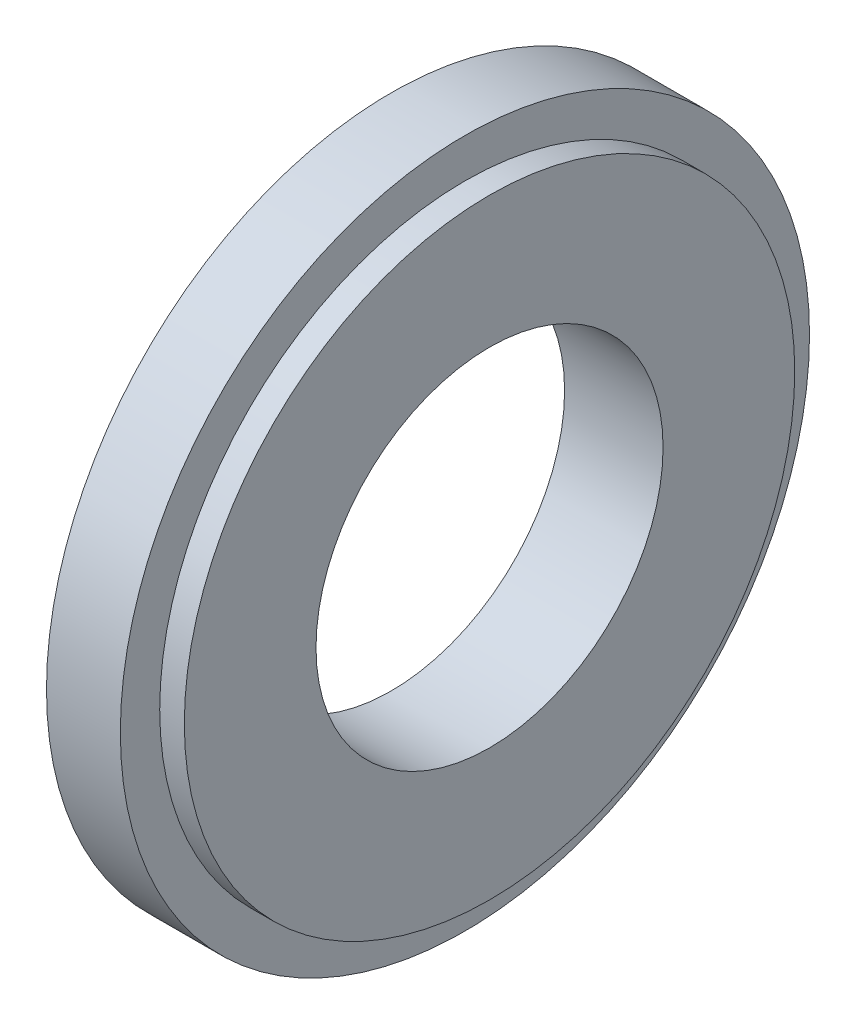
SolidWorks part; units mm, degrees
material "PEI"
ref_plane "Płaszczyzna przednia" through (0, 0, 0) normal (0, 0, 1) x (1, 0, 0)
ref_plane "Płaszczyzna górna" through (0, 0, 0) normal (0, 1, 0) x (1, 0, 0)
ref_plane "Płaszczyzna prawa" through (0, 0, 0) normal (1, 0, 0) x (0, 0, -1)
sketch "Szkic1" plane through (0, 0, 0) normal (0, 0, 1) x (1, 0, 0)
  line L0 (0, 0) -> (105558.8307, 0) construction
  line L1 (-100.3029, 0) -> (-100.3029, 70)
  line L2 (-100.3029, 70) -> (-85.3029, 70)
  line L3 (-85.3029, 70) -> (-85.3029, 62)
  line L4 (-85.3029, 62) -> (-80.3029, 62)
  line L5 (-80.3029, 62) -> (-80.3029, 0)
  line L6 (-100.3029, 0) -> (-80.3029, 0)
  dimension "D1" = 70
  dimension "D2" = 5
  dimension "D3" = 62
  dimension "D4" = 20
revolve "Obrót1" add sketch "Szkic1" angle 360 about L0
sketch "Szkic2" plane through (-80.3029, 0, 0) normal (1, 0, 0) x (0, 0, -1)
  circle A0 centre (0, 0) radius 35.25
  dimension "D1" = 70.5
extrude "Wytnij-wyciągnięcie1" cut sketch "Szkic2" against normal through all both and the other way through all contours A0
